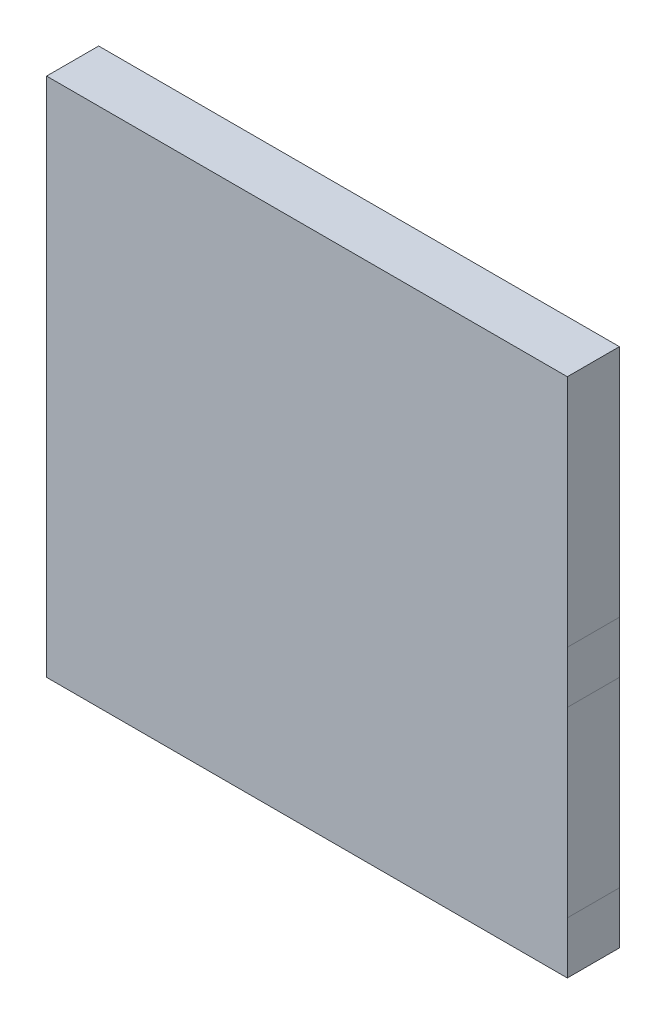
SolidWorks part; units mm, degrees
ref_plane "Front Plane" through (0, 0, 0) normal (0, 0, 1) x (1, 0, 0)
ref_plane "Top Plane" through (0, 0, 0) normal (0, 1, 0) x (1, 0, 0)
ref_plane "Right Plane" through (0, 0, 0) normal (1, 0, 0) x (0, 0, -1)
sketch "Sketch1" plane through (0, 0, 0) normal (0, 0, 1) x (1, 0, 0)
  line L1 (0, 0) -> (1000, 0)
  line L2 (0, 0) -> (0, 1000)
  line L3 (0, 1000) -> (1000, 1000)
  line L4 (1000, 0) -> (1000, 1000)
  dimension "D1" = 1000
  dimension "D2" = 1000
extrude "Boss-Extrude1" add sketch "Sketch1" along normal blind 100
sketch "Sketch2" plane through (1000, 0, 0) normal (1, 0, 0) x (0, 0, -1)
  line L0 (-100, 100) -> (0, 100)
  line L1 (-100, 0) -> (-100, 1000) construction
  line L2 (0, 0) -> (0, 1000) construction
  line L3 (-100, 450) -> (0, 450)
  line L4 (-100, 550) -> (0, 550)
  line L5 (-100, 0) -> (0, 0) construction
  dimension "D1" = 100
  dimension "D2" = 100
  dimension "D3" = 450
split line "Split Line1"
